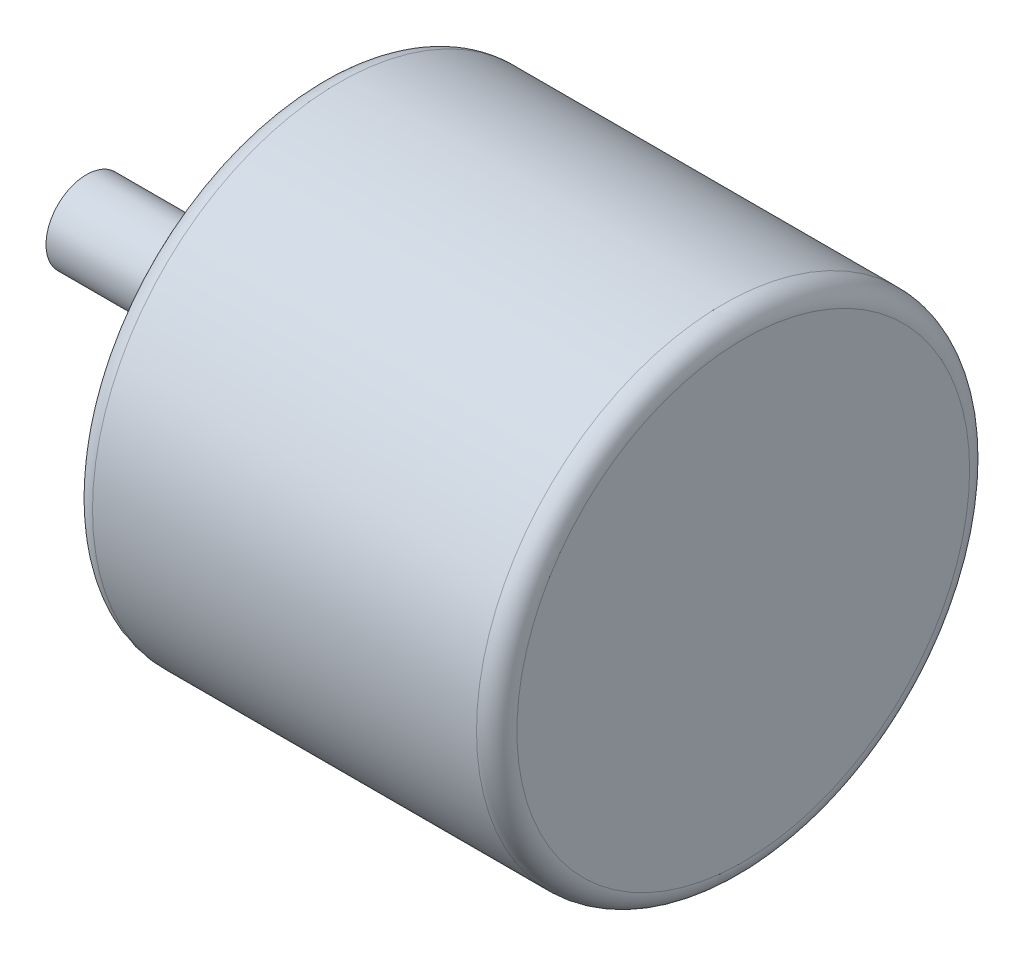
SolidWorks part; units mm, degrees
ref_plane "前视基准面" through (0, 0, 0) normal (0, 0, 1) x (1, 0, 0)
ref_plane "上视基准面" through (0, 0, 0) normal (0, 1, 0) x (1, 0, 0)
ref_plane "右视基准面" through (0, 0, 0) normal (1, 0, 0) x (0, 0, -1)
sketch "草图1" plane through (0, 0, 0) normal (1, 0, 0) x (0, 0, -1)
  circle A0 centre (0, 0) radius 12.2
  dimension "D1" = 24.4
extrude "凸台-拉伸1" add sketch "草图1" along normal blind 21
fillet "圆角1" radius 1 2 edges at (21, 0, -12.2) (0, 0, -12.2)
sketch "草图2" plane through (0, 0, 0) normal (-1, 0, 0) x (0, 0, 1)
  circle A0 centre (0, 0) radius 3.5
  dimension "D1" = 7
extrude "凸台-拉伸2" add sketch "草图2" along normal blind 2.5
sketch "草图3" plane through (-2.5, 0, 0) normal (-1, 0, 0) x (0, 0, 1)
  circle A0 centre (0, 0) radius 2
  dimension "D1" = 4
extrude "凸台-拉伸3" add sketch "草图3" along normal blind 9
